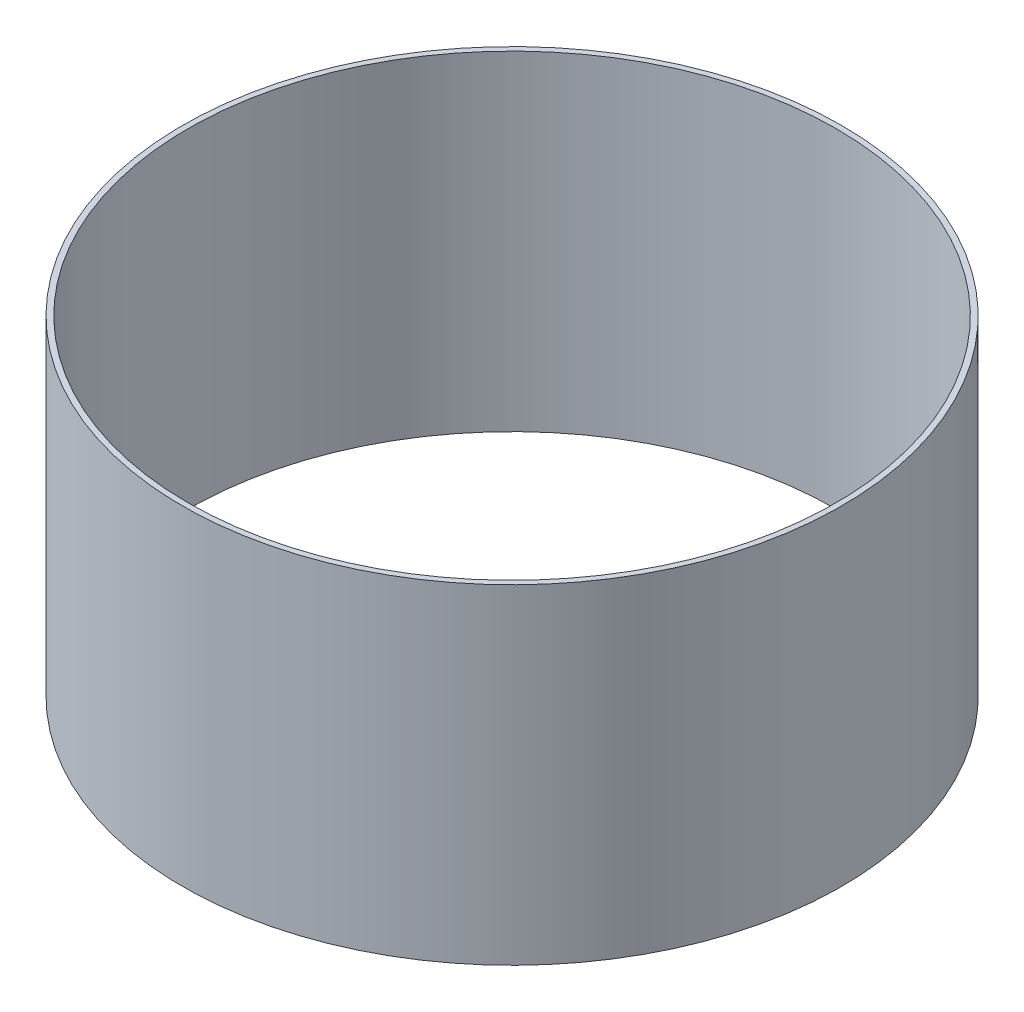
SolidWorks part; units mm, degrees
ref_plane "Front Plane" through (0, 0, 0) normal (0, 0, 1) x (1, 0, 0)
ref_plane "Top Plane" through (0, 0, 0) normal (0, 1, 0) x (1, 0, 0)
ref_plane "Right Plane" through (0, 0, 0) normal (1, 0, 0) x (0, 0, -1)
sketch "Sketch2" plane through (0, 0, 0) normal (0, 1, 0) x (1, 0, 0)
  circle A0 centre (0, 0) radius 74.93
  circle A1 centre (0, 0) radius 76.2
  dimension "D1" = 152.4
  dimension "D2" = 1.27
extrude "Boss-Extrude1" add sketch "Sketch2" along normal blind 76.2
